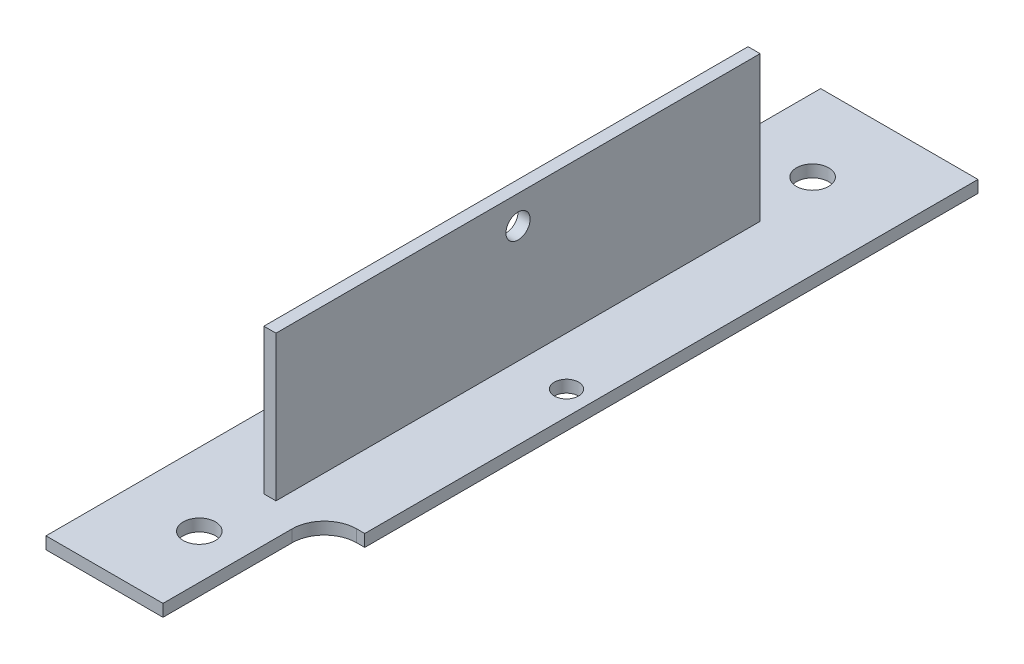
SolidWorks part; units mm, degrees
material "3.0205 (EN-AW 1200)"
ref_plane "Plan de face" through (0, 0, 0) normal (0, 0, 1) x (1, 0, 0)
ref_plane "Plan de dessus" through (0, 0, 0) normal (0, 1, 0) x (1, 0, 0)
ref_plane "Plan de droite" through (0, 0, 0) normal (1, 0, 0) x (0, 0, -1)
sketch "Esquisse1" plane through (0, 0, 0) normal (0, 0, 1) x (1, 0, 0)
  line L1 (-9.75, 0) -> (9.75, 0)
  dimension "D2" = 19.5
extrude "Extru.-Mince1" add sketch "Esquisse1" along normal blind 96 thin thin type one direction reverse wall 1.5
sketch "Esquisse2" plane through (0, 0, 0) normal (0, 0, -1) x (-1, 0, 0)
  line L0 (0, 0) -> (0, 19.5)
  dimension "D1" = 19.5
extrude "Extru.-Mince2" add sketch "Esquisse2" against normal up to surface (96 mm away) thin up to face at (0, 0.75, 96) thin type mid plane wall 1.5
sketch "Esquisse3" plane through (-0.75, 0, 0) normal (-1, 0, 0) x (0, 0, 1)
  line L0 (96, 19.5) -> (0, 19.5) construction
  line L1 (96, 0) -> (0, 0) construction
  line L2 (0, 1.5) -> (18, 1.5)
  line L3 (0, 1.5) -> (0, 19.5)
  line L4 (0, 19.5) -> (18, 19.5)
  line L5 (18, 1.5) -> (18, 19.5)
  line L6 (96, 1.5) -> (78, 1.5)
  line L7 (96, 1.5) -> (96, 19.5)
  line L8 (96, 19.5) -> (78, 19.5)
  line L9 (78, 1.5) -> (78, 19.5)
  line L10 (0, 1.5) -> (96, 1.5) construction
  circle A0 centre (48, 16) radius 1.5
  point P4 (48, 19.5)
  dimension "D1" = 16
  dimension "D2" = 3
  dimension "D3" = 60
  dimension "D4" = 60
  dimension "D5" = 90
extrude "Enlèv. mat.-Extru.1" cut sketch "Esquisse3" against normal blind 3
sketch "Esquisse4" plane through (0, 1.5, 0) normal (0, 1, 0) x (1, 0, 0)
  line L0 (-9.75, -48) -> (9.75, -48) construction
  line L5 (-9.75, -96) -> (-9.75, 0) construction
  line L6 (9.75, -96) -> (9.75, 0) construction
  line L7 (4.75, -96) -> (4.75, -76)
  line L8 (9.75, -76) -> (4.75, -76)
  line L9 (9.75, -96) -> (9.75, -76)
  line L10 (9.75, -96) -> (4.75, -96)
  line L13 (-0.75, -18) -> (-0.75, -78) construction
  circle A0 centre (-0.75, -10) radius 2
  circle A1 centre (-0.75, -86) radius 2
  circle A2 centre (6.75, -48) radius 1.5
  dimension "D1" = 76
  dimension "D2" = 4
  dimension "D3" = 3
  dimension "D6" = 3
  dimension "D4" = 5
  dimension "D5" = 20
extrude "Enlèv. mat.-Extru.2" cut sketch "Esquisse4" against normal blind 3
fillet "Congé1" radius 4 1 edges at (4.75, 0.75, 76)
